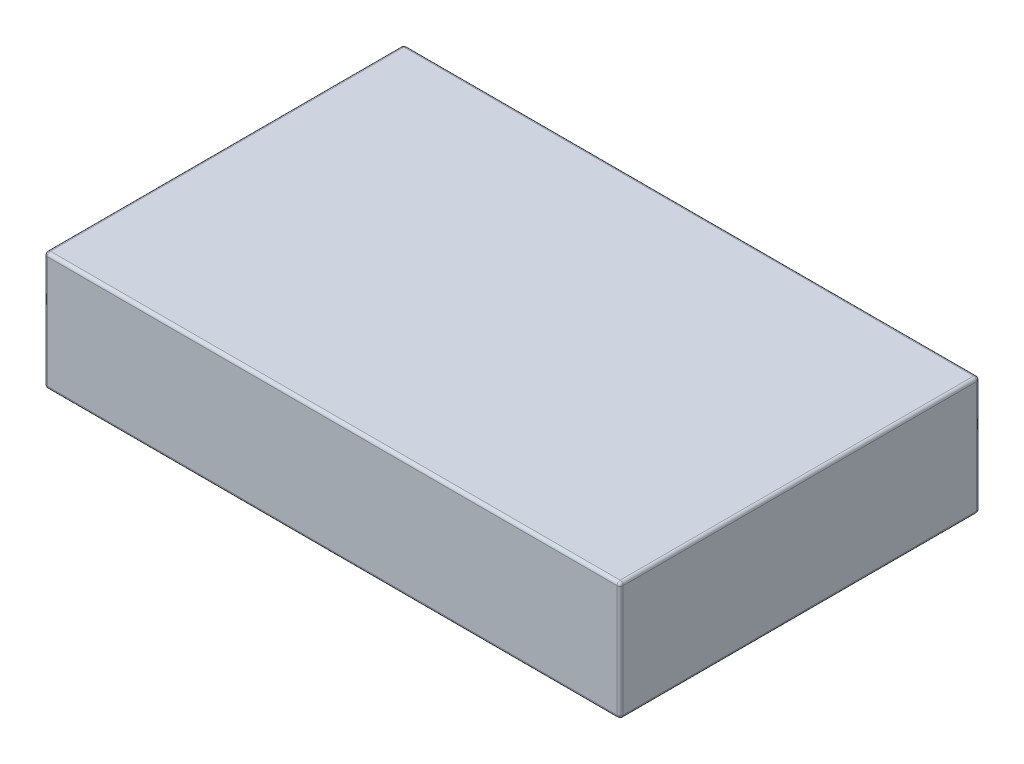
SolidWorks part; units mm, degrees
ref_plane "前视基准面" through (0, 0, 0) normal (0, 0, 1) x (1, 0, 0)
ref_plane "上视基准面" through (0, 0, 0) normal (0, 1, 0) x (1, 0, 0)
ref_plane "右视基准面" through (0, 0, 0) normal (1, 0, 0) x (0, 0, -1)
sketch "草图1" plane through (0, 0, 0) normal (0, 1, 0) x (1, 0, 0)
  line L1 (-182.5, 114) -> (182.5, 114)
  line L2 (-182.5, 114) -> (-182.5, -114)
  line L3 (-182.5, -114) -> (182.5, -114)
  line L4 (182.5, 114) -> (182.5, -114)
  dimension "D1" = 365
  dimension "D2" = 228
  dimension "D3" = 114
  dimension "D4" = 182.5
extrude "凸台-拉伸1" add sketch "草图1" along normal blind 75
sketch "草图2" plane through (-182.5, 0, 0) normal (-1, 0, 0) x (0, 0, 1)
  line L0 (-114, 37.5) -> (114, 37.5) construction
  line L1 (-114, 75) -> (-114, 0) construction
  line L2 (114, 75) -> (114, 0) construction
  line L3 (0, 75) -> (0, 0) construction
  line L4 (-114, 75) -> (114, 75) construction
  circle A0 centre (-86, 37.5) radius 7.5
  circle A1 centre (86, 37.5) radius 7.5
  dimension "D1" = 15
  dimension "D2" = 28
extrude "凸台-拉伸2" add sketch "草图2" along normal blind 15
fillet "圆角1" radius 2 12 edges at (182.5, 37.5, -114) (182.5, 37.5, 114) (182.5, 0, 0) (182.5, 75, 0) (0, 0, 114) (0, 75, 114) (0, 75, -114) (0, 0, -114) (-182.5, 37.5, -114) (-182.5, 37.5, 114) (-182.5, 0, 0) (-182.5, 75, 0)
